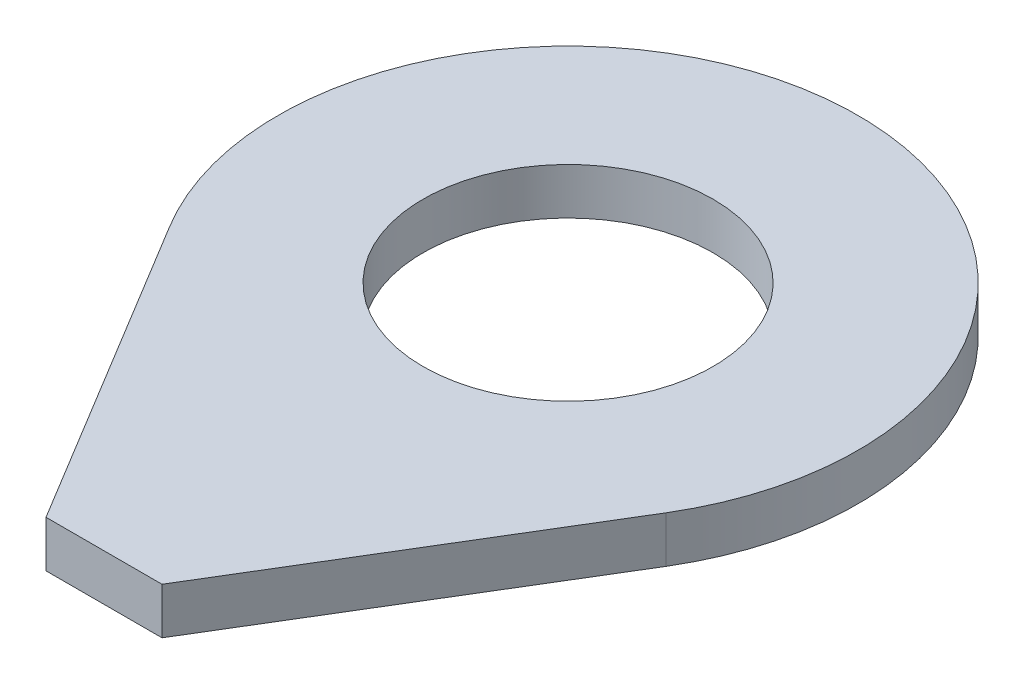
SolidWorks part; units mm, degrees
ref_plane "前视基准面" through (0, 0, 0) normal (0, 0, 1) x (1, 0, 0)
ref_plane "上视基准面" through (0, 0, 0) normal (0, 1, 0) x (1, 0, 0)
ref_plane "右视基准面" through (0, 0, 0) normal (1, 0, 0) x (0, 0, -1)
other "Configuration Table"
sketch "草图1" plane through (0, 0, 0) normal (0, 1, 0) x (1, 0, 0)
  line L0 (0, -5) -> (0, -8) construction
  line L1 (-4.2766, -2.5904) -> (-1, -8)
  line L2 (4.2766, -2.5904) -> (1, -8)
  line L3 (1, -8) -> (-1, -8)
  circle A0 centre (0, 0) radius 2.5
  arc A1 (4.2766, -2.5904) -> (-4.2766, -2.5904) centre (0, 0) ccw
  dimension "D1" = 10
  dimension "D2" = 5
  dimension "D3" = 1
  dimension "D4" = 1
  dimension "D5" = 3
extrude "凸台-拉伸1" add sketch "草图1" along normal blind 0.8
